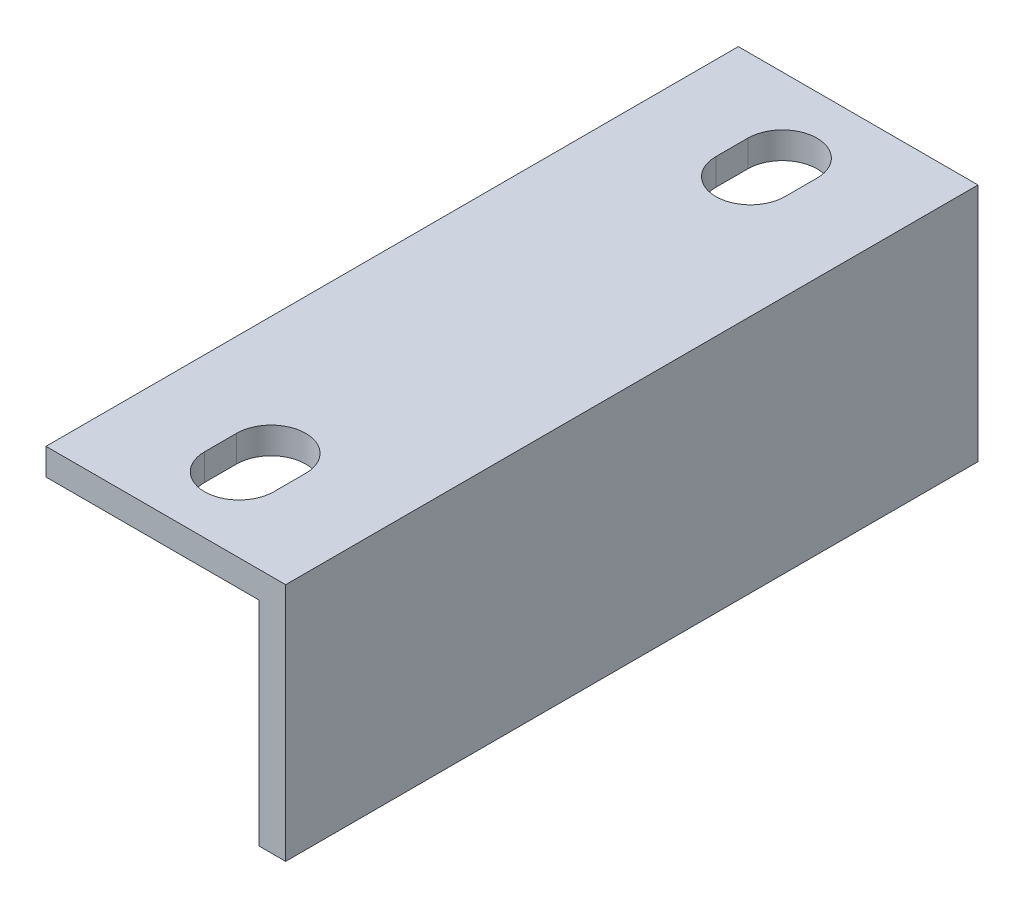
SolidWorks part; units mm, degrees
ref_plane "Front Plane" through (0, 0, 0) normal (0, 0, 1) x (1, 0, 0)
ref_plane "Top Plane" through (0, 0, 0) normal (0, 1, 0) x (1, 0, 0)
ref_plane "Right Plane" through (0, 0, 0) normal (1, 0, 0) x (0, 0, -1)
sketch "Sketch2" plane through (0, 0, 0) normal (0, 0, 1) x (1, 0, 0)
  line L0 (0, 0) -> (40, 0)
  line L1 (40, 0) -> (40, -40)
  line L2 (0, 5) -> (45, 5)
  line L3 (45, 5) -> (45, -40)
  line L4 (0, 0) -> (0, 5)
  line L5 (40, -40) -> (45, -40)
  dimension "D1" = 40
  dimension "D2" = 40
  dimension "D3" = 5
extrude "Boss-Extrude1" add sketch "Sketch2" along normal blind 130
sketch "Sketch3" plane through (0, 5, 0) normal (0, 1, 0) x (1, 0, 0)
  line L0 (22.2731, -14) -> (22.2731, -20) construction
  line L1 (28.7731, -14) -> (28.7731, -20)
  line L2 (15.7731, -14) -> (15.7731, -20)
  line L3 (0, -65) -> (28.7731, -65) construction
  line L4 (0, -130) -> (0, 0) construction
  line L5 (22.2731, -116) -> (22.2731, -110) construction
  line L6 (28.7731, -116) -> (28.7731, -110)
  line L7 (15.7731, -116) -> (15.7731, -110)
  arc A0 (28.7731, -14) -> (15.7731, -14) centre (22.2731, -14) ccw
  arc A1 (15.7731, -20) -> (28.7731, -20) centre (22.2731, -20) ccw
  arc A2 (28.7731, -116) -> (15.7731, -116) centre (22.2731, -116) cw
  arc A3 (15.7731, -110) -> (28.7731, -110) centre (22.2731, -110) cw
  point P2 (22.2731, -17)
  point P13 (22.2731, -113)
  dimension "D1" = 6.5
  dimension "D2" = 6.5
  dimension "D4" = 48
  dimension "D3" = 6
  dimension "D5" = 96
  dimension "D6" = 102
extrude "Cut-Extrude1" cut sketch "Sketch3" against normal blind 10
